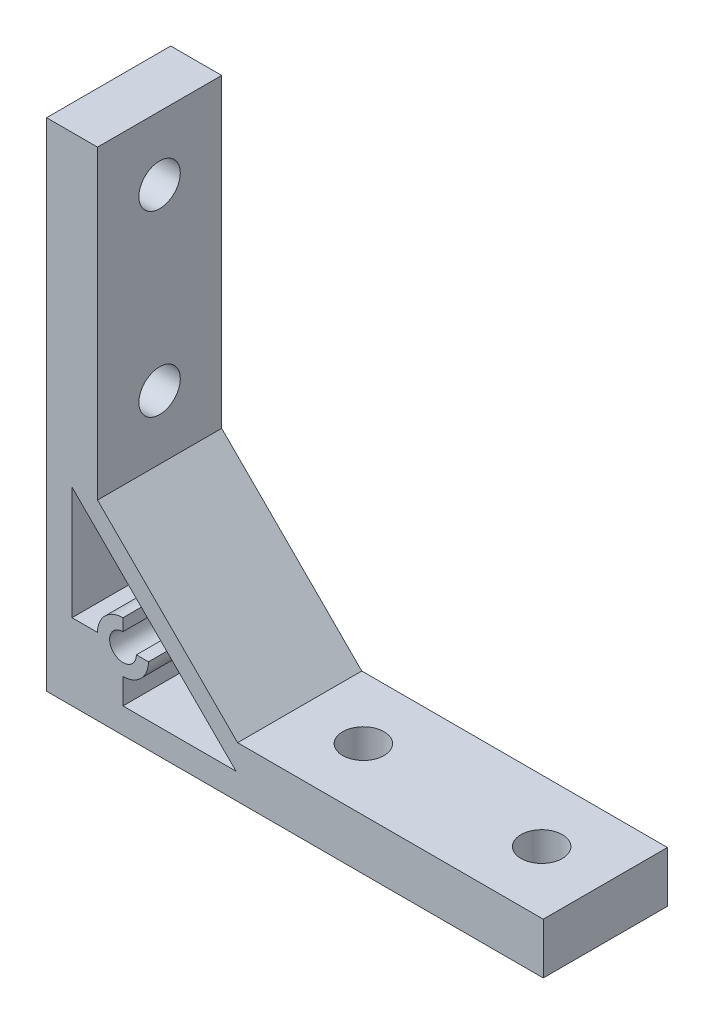
SolidWorks part; units mm, degrees
ref_plane "前视基准面" through (0, 0, 0) normal (0, 0, 1) x (1, 0, 0)
ref_plane "上视基准面" through (0, 0, 0) normal (0, 1, 0) x (1, 0, 0)
ref_plane "右视基准面" through (0, 0, 0) normal (1, 0, 0) x (0, 0, -1)
sketch "草图1" plane through (0, 0, 0) normal (0, 0, 1) x (1, 0, 0)
  line L0 (0, 0) -> (78, 0)
  line L1 (78, 0) -> (78, 8)
  line L2 (78, 8) -> (30, 8)
  line L3 (30, 8) -> (8, 30)
  line L4 (8, 30) -> (8, 78)
  line L5 (8, 78) -> (0, 78)
  line L6 (0, 78) -> (0, 0)
  dimension "D1" = 78
  dimension "D2" = 78
  dimension "D3" = 8
  dimension "D4" = 8
  dimension "D5" = 30
  dimension "D6" = 135
extrude "凸台-拉伸1" add sketch "草图1" along normal blind 19.5
sketch "草图2" plane through (0, 0, 19.5) normal (0, 0, 1) x (1, 0, 0)
  line L0 (4, 29.7574) -> (29.7574, 4)
  line L1 (29.7574, 4) -> (12, 4)
  line L2 (4, 12) -> (4, 29.7574)
  line L3 (4, 12) -> (12, 12)
  line L4 (12, 12) -> (12, 4)
  line L5 (30, 8) -> (8, 30) construction
  line L6 (0, 0) -> (78, 0) construction
  line L7 (0, 78) -> (0, 0) construction
  dimension "D1" = 3
  dimension "D2" = 4
  dimension "D3" = 12
  dimension "D4" = 4
extrude "切除-拉伸1" cut sketch "草图2" against normal up to next
sketch "草图3" plane through (0, 0, 19.5) normal (0, 0, 1) x (1, 0, 0)
  line L0 (12, 12) -> (12, 16)
  line L1 (12, 12) -> (16, 12)
  arc A0 (12, 16) -> (16, 12) centre (12, 12) ccw
  dimension "D1" = 8
extrude "凸台-拉伸2" add sketch "草图3" against normal up to surface (19.5 mm away) up to face at (12.3515, 12.3515, 0)
sketch "草图4" plane through (0, 0, 19.5) normal (0, 0, 1) x (1, 0, 0)
  circle A0 centre (12, 12) radius 2.1
  dimension "D1" = 4.2
extrude "切除-拉伸2" cut sketch "草图4" against normal up to next
sketch "草图5" plane through (0, 8, 0) normal (0, 1, 0) x (1, 0, 0)
  line L0 (-922, -9.75) -> (49078, -9.75) construction
  line L1 (78, -19.5) -> (78, 0) construction
  line L2 (0, -19.5) -> (0, 0) construction
  circle A0 centre (40, -9.75) radius 3.25
  circle A1 centre (68, -9.75) radius 3.25
  point P5 (78, -9.75)
  dimension "D1" = 6.5
  dimension "D2" = 6.5
  dimension "D3" = 40
  dimension "D4" = 28
extrude "切除-拉伸3" cut sketch "草图5" against normal up to next
sketch "草图6" plane through (8, 0, 0) normal (1, 0, 0) x (0, 0, -1)
  line L0 (-9.75, -922) -> (-9.75, 49078) construction
  line L1 (-19.5, 78) -> (0, 78) construction
  line L2 (-19.5, 0) -> (0, 0) construction
  circle A0 centre (-9.75, 68) radius 3.25
  circle A1 centre (-9.75, 40) radius 3.25
  point P5 (-9.75, 78)
  dimension "D1" = 6.5
  dimension "D2" = 6.5
  dimension "D3" = 40
  dimension "D4" = 28
extrude "切除-拉伸4" cut sketch "草图6" against normal up to next
